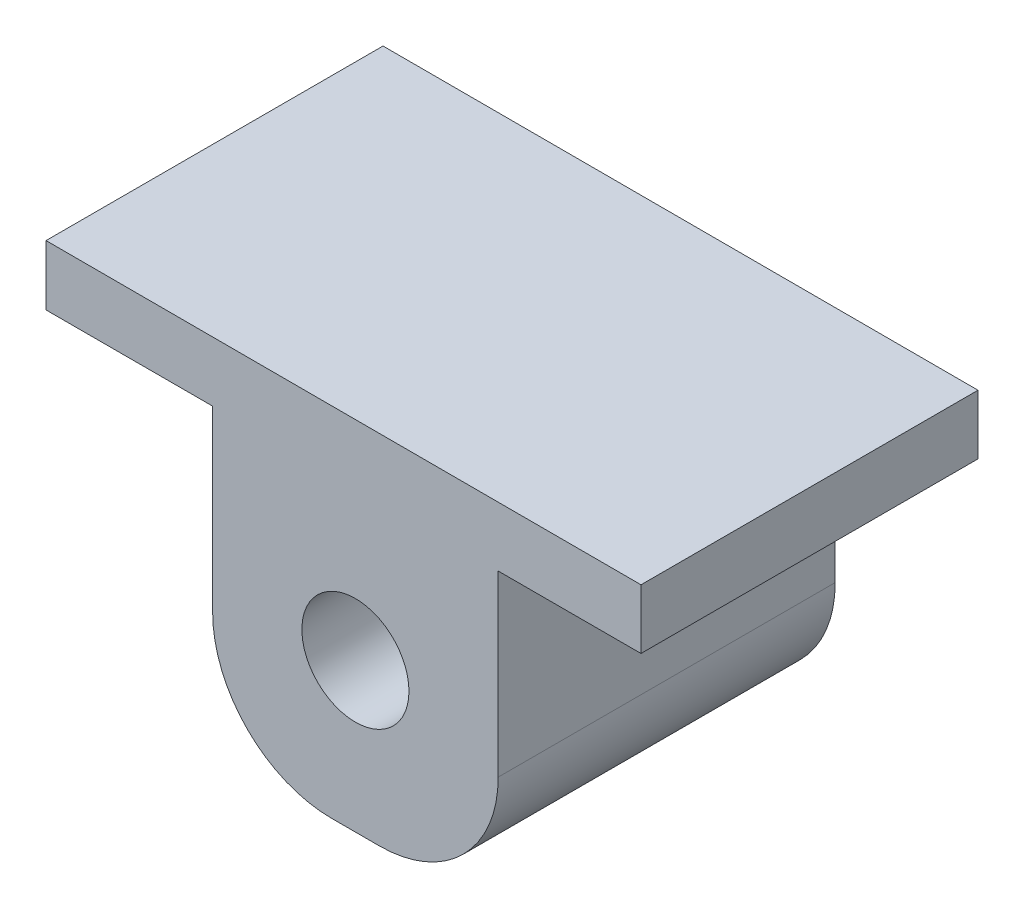
SolidWorks part; units mm, degrees
ref_plane "Alzado" through (0, 0, 0) normal (0, 0, 1) x (1, 0, 0)
ref_plane "Planta" through (0, 0, 0) normal (0, 1, 0) x (1, 0, 0)
ref_plane "Vista lateral" through (0, 0, 0) normal (1, 0, 0) x (0, 0, -1)
sketch "Croquis1" plane through (0, 0, 0) normal (0, 0, 1) x (1, 0, 0)
  line L0 (0.5278, 0.0056) -> (50.5278, -0.0449)
  line L1 (50.5278, -0.0449) -> (50.5278, -5.0449)
  line L2 (50.5278, -5.0449) -> (38.5278, -5.0449)
  line L3 (38.5278, -5.0449) -> (38.5278, -30.0449)
  line L4 (38.5278, -30.0449) -> (14.5278, -30.0449)
  line L5 (14.5278, -30.0449) -> (14.5278, -5.0449)
  line L6 (14.5278, -5.0449) -> (0.5247, -5.0449)
  line L7 (0.5247, -5.0449) -> (0.5278, 0.0056)
  circle A0 centre (26.5278, -17.5449) radius 4.5
  point P10 (0, 0)
  point P11 (0, 0)
  point P12 (0, 0)
  point P13 (0, 0)
  dimension "D5" = 9
  dimension "D1" = 50
  dimension "D2" = 12
  dimension "D3" = 12.5
  dimension "D4" = 25
  dimension "D6" = 5
  dimension "D7" = 24
  dimension "D8" = 12
  dimension "D9" = 12
extrude "Saliente-Extruir1" add sketch "Croquis1" along normal blind 28.32
fillet "Redondeo1" radius 10 2 edges at (14.5278, -30.0449, 14.16) (38.5278, -30.0449, 14.16)
